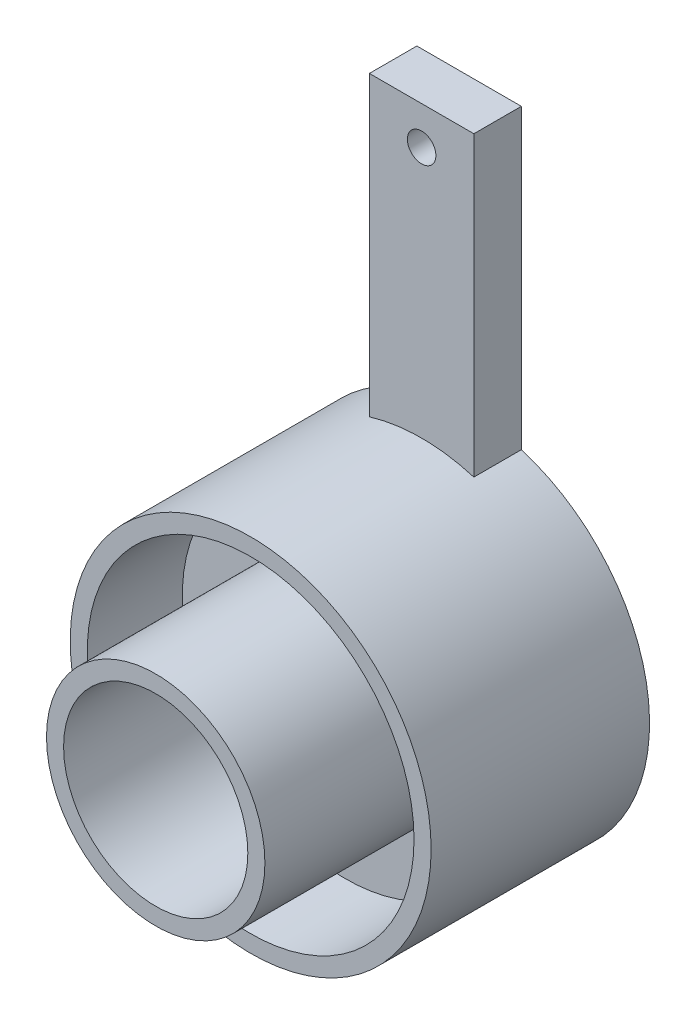
SolidWorks part; units mm, degrees
ref_plane "Alzado" through (0, 0, 0) normal (0, 0, 1) x (1, 0, 0)
ref_plane "Planta" through (0, 0, 0) normal (0, 1, 0) x (1, 0, 0)
ref_plane "Vista lateral" through (0, 0, 0) normal (1, 0, 0) x (0, 0, -1)
sketch "Croquis1" plane through (0, 0, 0) normal (0, 0, 1) x (1, 0, 0)
  circle A0 centre (0, 0) radius 19
  dimension "D1" = 38
extrude "Saliente-Extruir1" add sketch "Croquis1" along normal blind 23
sketch "Croquis2" plane through (0, 0, 23) normal (0, 0, 1) x (1, 0, 0)
  circle A0 centre (0, 0) radius 17.2
  dimension "D1" = 34.4
extrude "Cortar-Extruir1" cut sketch "Croquis2" against normal blind 10
sketch "Croquis3" plane through (0, 0, 13) normal (0, 0, 1) x (1, 0, 0)
  circle A0 centre (0, 0) radius 11.5
  circle A1 centre (0, 0) radius 9.7
  dimension "D1" = 23
  dimension "D2" = 19.4
extrude "Saliente-Extruir2" add sketch "Croquis3" along normal blind 20
sketch "Croquis4" plane through (0, 0, 0) normal (0, 0, -1) x (-1, 0, 0)
  circle A0 centre (0, 0) radius 17.2
  dimension "D1" = 34.4
extrude "Cortar-Extruir3" cut sketch "Croquis4" against normal blind 10
sketch "Croquis5" plane through (0, 0, 10) normal (0, 0, -1) x (-1, 0, 0)
  circle A0 centre (0, 0) radius 11.5
  circle A1 centre (0, 0) radius 9.7
  dimension "D1" = 23
  dimension "D2" = 19.4
extrude "Saliente-Extruir3" add sketch "Croquis5" along normal blind 10
sketch "Croquis6" plane through (0, 0, 0) normal (1, 0, 0) x (0, 0, -1)
  line L0 (0, 0) -> (0, 11.5)
  line L1 (-5, 10.7024) -> (-5, 10.0086)
  line L4 (-5, 10.7024) -> (-5, 11.5)
  line L5 (0, 11.5) -> (0, 49.5)
  line L6 (0, -19) -> (0, 19) construction
  line L7 (0, 49.5) -> (-5, 49.5)
  line L8 (-5, 49.5) -> (-5, 10.7024)
  line L9 (-5, 10.0086) -> (0, 10.0086)
  line L10 (0, 10.0086) -> (0, 10.7024)
  dimension "D1" = 5
  dimension "D2" = 38
extrude "Saliente-Extruir4" add sketch "Croquis6" along normal mid plane 11
sketch "Croquis7" plane through (0, 0, 0) normal (0, 0, -1) x (-1, 0, 0)
  line L0 (-13.0534, -11.2004) -> (-5.9668, -4.1448)
  line L1 (-5.9668, -4.1448) -> (-6.8709, -2.3608)
  line L2 (-6.8709, -2.3608) -> (-16.7512, -3.9035)
  circle A0 centre (0, 0) radius 17.2 construction
  arc A1 (-5.5, 16.2969) -> (5.5, 16.2969) centre (0, 0) ccw construction
  arc A2 (-16.7512, -3.9035) -> (-13.0534, -11.2004) centre (0, 0) ccw
  dimension "D1" = 10
  dimension "D2" = 10
  dimension "D3" = 2
  dimension "D4" = 108
  dimension "D5" = 108
extrude "Saliente-Extruir5" add sketch "Croquis7" against normal blind 2.4
sketch "Croquis8" plane through (0, 0, 0) normal (0, 0, -1) x (-1, 0, 0)
  line L0 (-5.5, 49.5) -> (5.5, 49.5) construction
  circle A0 centre (0, 45.5) radius 1.5
  dimension "D2" = 3
  dimension "D1" = 4
extrude "Cortar-Extruir4" cut sketch "Croquis8" against normal through all
